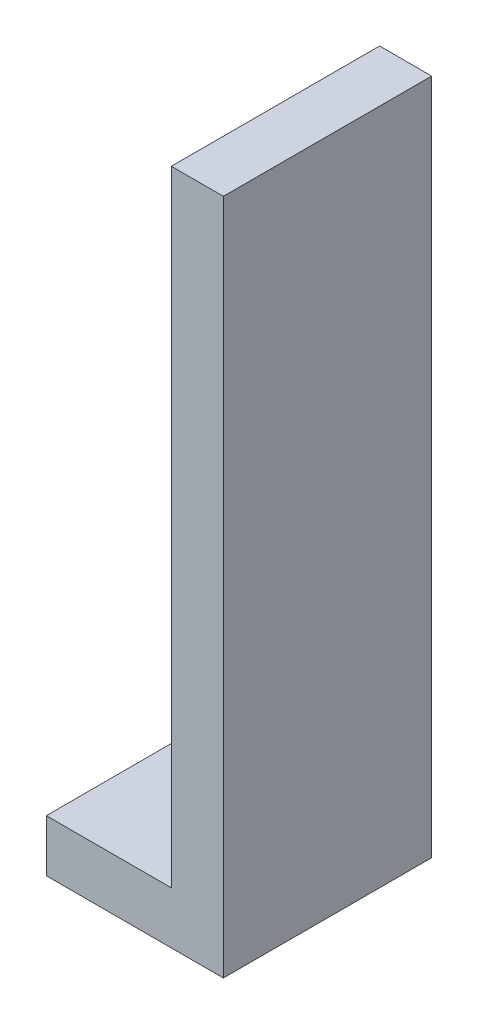
SolidWorks part; units mm, degrees
ref_plane "Ön Düzlem" through (0, 0, 0) normal (0, 0, 1) x (1, 0, 0)
ref_plane "Üst Düzlem" through (0, 0, 0) normal (0, 1, 0) x (1, 0, 0)
ref_plane "Sağ Düzlem" through (0, 0, 0) normal (1, 0, 0) x (0, 0, -1)
sketch "Çizim1" plane through (0, 0, 0) normal (0, 0, 1) x (1, 0, 0)
  line L0 (0, 0) -> (12, 0)
  line L1 (0, 0) -> (0, 60)
  line L2 (0, 60) -> (-5, 60)
  line L3 (-5, 60) -> (-5, -5)
  line L4 (-5, -5) -> (12, -5)
  line L5 (12, -5) -> (12, 0)
  dimension "D1" = 12
  dimension "D2" = 17
  dimension "D3" = 5
  dimension "D4" = 5
  dimension "D5" = 65
extrude "Yükseklik-Ekstrüzyon1" add sketch "Çizim1" along normal blind 20
sketch "Çizim2" plane through (0, 0, 0) normal (0, 1, 0) x (1, 0, 0)
  circle A0 centre (6, -10) radius 1.7
extrude "Kes-Ekstrüzyon1" cut sketch "Çizim2" against normal blind 20
ref_plane "Düzlem1" through (-5, 0, 0) normal (1, 0, 0) x (0, 0, -1)
mirror "Aynalama1" about plane through (-5, 0, 0) normal (1, 0, 0) of "Kes-Ekstrüzyon1", "Yükseklik-Ekstrüzyon1"
sketch "Çizim3" plane through (0, -5, 0) normal (0, -1, 0) x (1, 0, 0)
  line L0 (-22, 20) -> (12, 20) construction
  line L1 (-5, 20) -> (18.7544, 20)
  line L2 (-5, 20) -> (-5, -6.4391)
  line L3 (-5, -6.4391) -> (18.7544, -6.4391)
  line L4 (18.7544, 20) -> (18.7544, -6.4391)
extrude "Kes-Ekstrüzyon2" cut sketch "Çizim3" against normal blind 82
